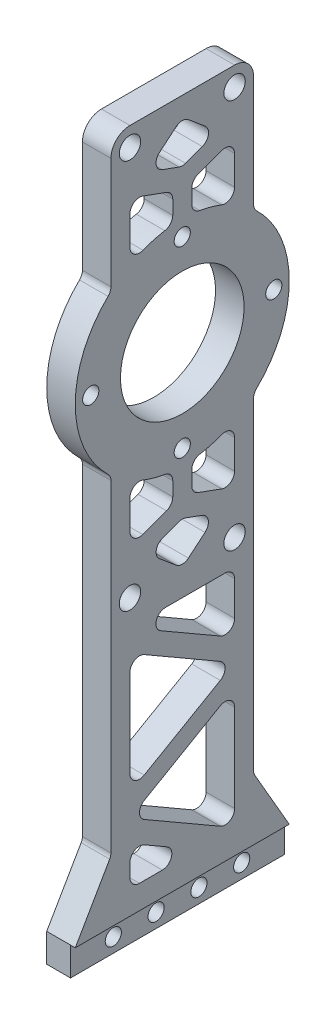
SolidWorks part; units mm, degrees
material "Сплав 2024"
ref_plane "Спереди" through (0, 0, 0) normal (0, 0, 1) x (1, 0, 0)
ref_plane "Сверху" through (0, 0, 0) normal (0, 1, 0) x (1, 0, 0)
ref_plane "Справа" through (0, 0, 0) normal (1, 0, 0) x (0, 0, -1)
sketch "Эскиз1" plane through (0, 0, 0) normal (0, 1, 0) x (1, 0, 0)
  line L1 (0, 0) -> (6, 0)
  line L2 (0, 0) -> (0, -30)
  line L3 (0, -30) -> (6, -30)
  line L4 (6, 0) -> (6, -30)
  dimension "D1" = 6
  dimension "D2" = 30
extrude "Бобышка-Вытянуть1" add sketch "Эскиз1" along normal blind 177
sketch "Эскиз2" plane through (0, 0, 0) normal (-1, 0, 0) x (0, 0, 1)
  line L0 (30, 105) -> (0, 105) construction
  line L3 (15, 177) -> (15, 0) construction
  line L4 (0, 177) -> (30, 177) construction
  line L5 (0, 0) -> (30, 0) construction
  line L6 (30, 0) -> (0, 0) construction
  circle A0 centre (15, 105) radius 22.5
  dimension "D1" = 45
  dimension "D2" = 105
extrude "Бобышка-Вытянуть2" add sketch "Эскиз2" against normal up to surface (6 mm away) up to face at (6, 88.5, 15)
sketch "Эскиз3" plane through (0, 0, 0) normal (-1, 0, 0) x (0, 0, 1)
  circle A0 centre (15, 105) radius 13
  dimension "D1" = 26
extrude "Вырез-Вытянуть1" cut sketch "Эскиз3" against normal through all
sketch "Эскиз4" plane through (6, 0, 0) normal (-1, 0, 0) x (0, 0, 1)
  line L0 (-7.5, 105) -> (37.5, 105) construction
  line L2 (15, 127.5) -> (15, 82.5) construction
  line L3 (30, 105) -> (0, 105) construction
  circle A0 centre (15, 105) radius 19.25 construction
  circle A1 centre (15, 105) radius 22.5 construction
  dimension "D1" = 38.5
  dimension "D2" = 90
hole_wizard "Отверстие с зазором M32" positions "Эскиз6" profile "Эскиз5" hole size "M3" standard "Ansi Metric" end condition up to next
sketch "Эскиз6" plane through (6, -25.0247, 7.2629) normal (-1, 0, 0) x (0, 0, 1)
  line L0 (-14.7629, 130.0247) -> (30.2371, 130.0247) construction
  line L1 (7.7371, 152.5247) -> (7.7371, 107.5247) construction
  circle A0 centre (7.7371, 130.0247) radius 19.25 construction
  point P0 (-11.5129, 130.0247)
  point P6 (7.7371, 110.7747)
  point P10 (26.9871, 130.0247)
  point P12 (7.7371, 149.2747)
sketch "Эскиз5" plane through (6, 105, -4.25) normal (0, 1, 0) x (0, 0, -1)
  line L0 (0, 0) -> (0, 6)
  line L1 (0, 6) -> (1.7, 6)
  line L2 (1.7, 6) -> (1.7, 0)
  line L5 (1.7, 0) -> (0, 0)
  line L11 (0, -6.35) -> (0, 107.95) construction
  dimension "Диаметр сквозного отверстия" = 3.4
  dimension "Глубина сквозного отверстия" = 6
sketch "Эскиз8" plane through (6, 0, 0) normal (1, 0, 0) x (0, 0, -1)
  line L0 (-15, 177) -> (-15, 0) construction
  line L1 (-30, 177) -> (0, 177) construction
  line L2 (-30, 0) -> (0, 0) construction
  line L3 (19.447, 105) -> (-49.447, 105) construction
  line L4 (0, 177) -> (0, 121.7705) construction
  line L5 (-26, 146) -> (-4, 146) construction
  line L6 (-26, 146) -> (-26, 64) construction
  line L7 (-26, 64) -> (-4, 64) construction
  line L8 (-4, 146) -> (-4, 64) construction
  line L9 (-26, 146) -> (-4, 64) construction
  line L11 (-30, 105) -> (0, 105) construction
  point P8 (-15, 105)
  point P9 (-15, 105)
  dimension "D1" = 4
  dimension "D2" = 82
  dimension "D4" = 22
hole_wizard "Отверстие с зазором M41" positions "Эскиз10" profile "Эскиз9" hole size "M4" standard "Ansi Metric" end condition through all
sketch "Эскиз10" plane through (6, 0, 0) normal (1, 0, 0) x (0, 0, -1)
  point P0 (-26, 146)
  point P3 (-4, 146)
  point P6 (-4, 64)
  point P9 (-26, 64)
sketch "Эскиз9" plane through (6, 146, 26) normal (0, 1, 0) x (0, 0, -1)
  line L0 (0, 0) -> (0, 6)
  line L1 (0, 6) -> (2.25, 6)
  line L2 (2.25, 6) -> (2.25, 0)
  line L5 (2.25, 0) -> (0, 0)
  line L11 (0, -6.35) -> (0, 107.95) construction
  dimension "Диаметр сквозного отверстия" = 4.5
  dimension "Глубина сквозного отверстия" = 6
sketch "Эскиз11" plane through (6, 0, 0) normal (1, 0, 0) x (0, 0, -1)
  line L0 (-30, 0) -> (0, 0) construction
  line L1 (-15, 177) -> (-15, 0) construction
  line L2 (-30, 177) -> (0, 177) construction
  line L3 (0, 88.2295) -> (0, 0) construction
  line L4 (-30, 88.2295) -> (-30, 0) construction
  line L5 (-37.5, 3) -> (7.5, 3) construction
  line L20 (-1.5, 0) -> (-1.5, 6) construction
  line L21 (-10.5, 0) -> (-10.5, 6) construction
  line L22 (-19.5, 0) -> (-19.5, 6) construction
  line L23 (-28.5, 0) -> (-28.5, 6) construction
  line L25 (-37.5, 0) -> (7.5, 6) construction
  line L26 (-37.5, 6) -> (7.5, 0) construction
  line L27 (-37.5, 6) -> (7.5, 6) construction
  line L28 (0, 18.9904) -> (7.5, 6)
  line L29 (-30, 18.9904) -> (0, 18.9904)
  line L30 (7.5, 6) -> (7.5, 0)
  line L31 (-37.5, 0) -> (7.5, 0)
  line L32 (-37.5, 6) -> (-37.5, 0)
  line L33 (-37.5, 6) -> (-30, 18.9904)
  point P2 (-15, 3)
  dimension "D1" = 45
  dimension "D2" = 6
  dimension "D3" = 9
  dimension "D4" = 9
  dimension "D5" = 9
  dimension "D6" = 9
  dimension "D7" = 120
extrude "Бобышка-Вытянуть3" add sketch "Эскиз11" against normal up to surface (6 mm away) up to face at (0, 146, 23.75)
hole_wizard "Отверстие с зазором M31" positions "Эскиз13" profile "Эскиз12" hole size "M3" standard "Ansi Metric" end condition through all
sketch "Эскиз13" plane through (6, 0, 0) normal (1, 0, 0) x (0, 0, -1)
  line L4 (-28.5, 0) -> (-28.5, 6) construction
  line L5 (-19.5, 0) -> (-19.5, 6) construction
  line L6 (-10.5, 0) -> (-10.5, 6) construction
  line L7 (-1.5, 0) -> (-1.5, 6) construction
  point P16 (-28.5, 3)
  point P20 (-19.5, 3)
  point P24 (-10.5, 3)
  point P28 (-1.5, 3)
sketch "Эскиз12" plane through (6, 3, 28.5) normal (0, 1, 0) x (0, 0, -1)
  line L0 (0, 0) -> (0, 6)
  line L1 (0, 6) -> (1.7, 6)
  line L2 (1.7, 6) -> (1.7, 0)
  line L5 (1.7, 0) -> (0, 0)
  line L11 (0, -6.35) -> (0, 107.95) construction
  dimension "Диаметр сквозного отверстия" = 3.4
  dimension "Глубина сквозного отверстия" = 6
sketch "Эскиз14" plane through (6, 0, 0) normal (1, 0, 0) x (0, 0, -1)
  line L5 (-37.5, 0) -> (7.5, 0)
  line L6 (-37.5, 0) -> (-37.5, 6)
  line L7 (-37.5, 6) -> (7.5, 6)
  line L8 (7.5, 0) -> (7.5, 6)
extrude "Вырез-Вытянуть2" cut sketch "Эскиз14" against normal blind 1
sketch "Эскиз15" plane through (6, 0, 0) normal (1, 0, 0) x (0, 0, -1)
  line L0 (0, 177) -> (0, 121.7705) construction
  line L1 (-30, 177) -> (0, 177)
  line L2 (-30, 177) -> (-30, 150.0245)
  line L3 (-30, 150.0245) -> (0, 150.0245)
  line L4 (0, 177) -> (0, 150.0245)
  circle A0 centre (-26, 146) radius 2.25 construction
  dimension "D1" = 4.0245
extrude "Вырез-Вытянуть3" cut sketch "Эскиз15" against normal up to surface (6 mm away) up to face at (0, 3, 26.8)
fillet "Скругление1" radius 4 2 edges at (3, 150.0245, 30) (3, 150.0245, 0)
sketch "Эскиз16" plane through (0, 0, 0) normal (-1, 0, 0) x (0, 0, 1)
  line L0 (4, 0) -> (4, 150.0245) construction
  line L1 (-7.5, 0) -> (37.5, 0) construction
  line L2 (4, 150.0245) -> (26, 150.0245) construction
  line L3 (26, 0) -> (26, 150.0245) construction
  line L4 (0, 88.2295) -> (0, 18.9904) construction
  line L5 (30, 88.2295) -> (30, 18.9904) construction
  line L6 (15, 177) -> (15, 0) construction
  line L7 (0, 146.0245) -> (30, 146.0245) construction
  line L8 (0, 146.0245) -> (0, 121.7705) construction
  line L9 (30, 146.0245) -> (30, 121.7705) construction
  line L10 (15, 146.0245) -> (4, 136.7944) construction
  line L11 (15, 146.0245) -> (26, 136.7944) construction
  line L12 (0, 136.7944) -> (30, 136.7944) construction
  line L13 (4, 136.7944) -> (4, 124.6278)
  line L14 (26, 136.7944) -> (26, 124.6278)
  line L15 (13, 133.5187) -> (13, 127.4109)
  line L16 (17, 133.5187) -> (17, 127.4109)
  line L17 (4, 136.7944) -> (13, 133.5187)
  line L18 (0, 133.5187) -> (30, 133.5187) construction
  line L19 (26, 136.7944) -> (17, 133.5187)
  line L20 (7.5382, 139.7634) -> (15, 137.0475)
  line L21 (22.4618, 139.7634) -> (15, 137.0475)
  line L22 (7.5382, 139.7634) -> (15, 146.0245)
  line L23 (15, 146.0245) -> (22.4618, 139.7634)
  line L24 (15, 105) -> (22.4618, 105) construction
  line L25 (13, 76.4791) -> (13, 82.5891)
  line L26 (17, 76.4791) -> (17, 82.5891)
  line L27 (26, 73.2033) -> (17, 76.4791)
  line L28 (26, 73.2033) -> (26, 85.3722)
  line L29 (4, 73.2033) -> (4, 85.3722)
  line L30 (4, 73.2033) -> (13, 76.4791)
  line L31 (7.5605, 70.2425) -> (15, 72.9503)
  line L32 (22.4395, 70.2425) -> (15, 72.9503)
  line L33 (15, 64) -> (22.4395, 70.2425)
  line L34 (7.5605, 70.2425) -> (15, 64)
  line L35 (26, 53.8812) -> (26, 28.4778)
  line L36 (26, 28.4778) -> (4, 41.1795)
  line L37 (4, 41.1795) -> (26, 53.8812)
  line L38 (4, 58.5) -> (26, 58.5)
  line L39 (26, 58.5) -> (4, 45.7983)
  line L40 (4, 45.7983) -> (4, 58.5)
  line L41 (4, 36.5607) -> (26, 23.859)
  line L42 (26, 23.859) -> (4, 11.1573)
  line L43 (4, 11.1573) -> (4, 36.5607)
  line L44 (11.7276, 11) -> (26, 19.2402)
  line L45 (26, 19.2402) -> (26, 11)
  line L46 (26, 11) -> (11.7276, 11)
  line L47 (34.6132, 11) -> (-4.6132, 11) construction
  line L48 (30, 18.9904) -> (37.5, 6) construction
  line L49 (-7.5, 6) -> (0, 18.9904) construction
  line L50 (-7.5, 6) -> (37.5, 6) construction
  line L51 (0, 76.4791) -> (30, 76.4791) construction
  line L52 (0, 73.2033) -> (30, 73.2033) construction
  line L53 (0, 70.2425) -> (30, 70.2425) construction
  line L54 (26, 64) -> (4, 64) construction
  circle A0 centre (15, 105) radius 22.5 construction
  arc A1 (4, 124.6278) -> (13, 127.4109) centre (15, 105) cw
  arc A2 (17, 127.4109) -> (26, 124.6278) centre (15, 105) cw
  arc A3 (17, 82.5891) -> (26, 85.3722) centre (15, 105) ccw
  arc A4 (4, 85.3722) -> (13, 82.5891) centre (15, 105) ccw
  circle A5 centre (4, 64) radius 2.25 construction
  point P12 (4, 124.6278)
  point P13 (26, 124.6278)
  point P20 (15, 146.0245)
  dimension "D3" = 4
  dimension "D16" = 5.5
  dimension "D1" = 4
  dimension "D2" = 4
  dimension "D4" = 100
  dimension "D5" = 4
  dimension "D6" = 2
  dimension "D7" = 4
  dimension "D8" = 110
  dimension "D9" = 30
  dimension "D10" = 4
  dimension "D11" = 4
  dimension "D12" = 4
  dimension "D13" = 60
  dimension "D14" = 60
  dimension "D15" = 5
  dimension "D17" = 6.11
  dimension "D18" = 4
  dimension "D19" = 2
  dimension "D20" = 110
  dimension "D21" = 4
  dimension "D22" = 100
extrude "Вырез-Вытянуть4" cut sketch "Эскиз16" against normal through all
fillet "Скругление3" radius 2 42 edges at (3, 127.4109, 13) (3, 124.6278, 26) (3, 124.6278, 4) (3, 127.4109, 17) (3, 133.5187, 17) (3, 136.7944, 4) (3, 133.5187, 13) (3, 136.7944, 26) (3, 137.0475, 15) (3, 139.7634, 22.4618) (3, 139.7634, 7.5382) (3, 146.0245, 15) (3, 70.2425, 7.5605) (3, 70.2425, 22.4395) (3, 85.3722, 4) (3, 76.4791, 17) (3, 82.5891, 17) (3, 73.2033, 4) (3, 64, 15) (3, 72.9503, 15) (3, 82.5891, 13) (3, 85.3722, 26) (3, 76.4791, 13) (3, 73.2033, 26) (3, 11, 11.7276) (3, 11, 26) (3, 11.1573, 4) (3, 19.2402, 26) (3, 23.859, 26) (3, 28.4778, 26) (3, 36.5607, 4) (3, 53.8812, 26) (3, 41.1795, 4) (3, 45.7983, 4) (3, 58.5, 4) (3, 58.5, 26) (3, 18.9904, 30) (3, 18.9904, 0) (3, 121.7705, 0) (3, 88.2295, 0) (3, 88.2295, 30) (3, 121.7705, 30)
equation "\"D4@Эскиз11\"=\"D3@Эскиз11\""
equation "\"D5@Эскиз11\"=\"D3@Эскиз11\""
equation "\"D6@Эскиз11\"=\"D4@Эскиз11\""
equation "\"D3@Эскиз11\" = \"D1@Эскиз11\" / 5"
equation "\"D13@Эскиз16\"=\"D9@Эскиз16\"*2"
equation "\"D11@Эскиз16\"=\"D10@Эскиз16\""
equation "\"D12@Эскиз16\"=\"D10@Эскиз16\""
